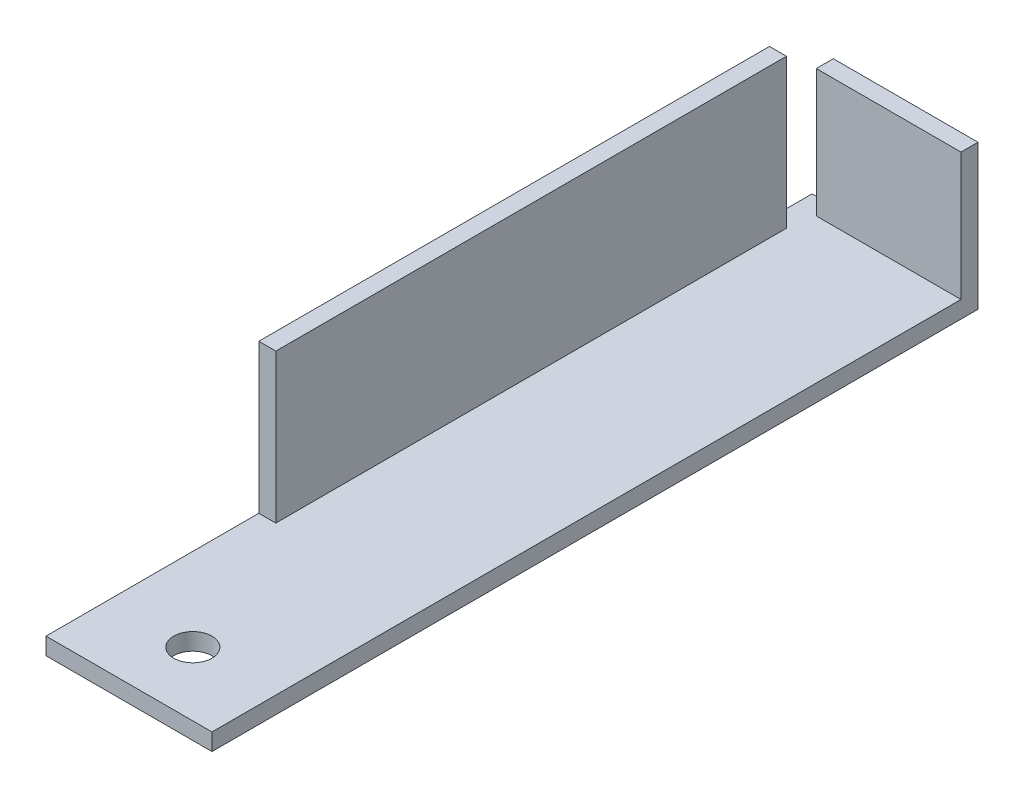
SolidWorks part; units mm, degrees
ref_plane "Front Plane" through (0, 0, 0) normal (0, 0, 1) x (1, 0, 0)
ref_plane "Top Plane" through (0, 0, 0) normal (0, 1, 0) x (1, 0, 0)
ref_plane "Right Plane" through (0, 0, 0) normal (1, 0, 0) x (0, 0, -1)
sketch "Sketch1" plane through (0, 0, 0) normal (0, 0, 1) x (1, 0, 0)
  line L0 (0, 0) -> (0, 19.5)
  line L1 (0, 19.5) -> (2, 19.5)
  line L2 (2, 19.5) -> (2, 2)
  line L3 (2, 2) -> (19.5, 2)
  line L4 (19.5, 2) -> (19.5, 0)
  line L5 (19.5, 0) -> (0, 0)
  dimension "D1" = 19.5
  dimension "D2" = 2
extrude "Boss-Extrude1" add sketch "Sketch1" along normal blind 90
sketch "Sketch8" plane through (2, 0, 0) normal (1, 0, 0) x (0, 0, -1)
  line L0 (-90, 2) -> (0, 2) construction
  line L1 (-90, 19.5) -> (-65, 19.5)
  line L2 (-90, 19.5) -> (-90, 2)
  line L3 (-90, 2) -> (-65, 2)
  line L4 (-65, 19.5) -> (-65, 2)
  line L5 (-90, 2) -> (0, 2) construction
  line L6 (0, 19.5) -> (-5, 19.5)
  line L7 (0, 19.5) -> (0, 2)
  line L8 (0, 2) -> (-5, 2)
  line L9 (-5, 19.5) -> (-5, 2)
  dimension "D1" = 60
  dimension "D2" = 5
extrude "Cut-Extrude1" cut sketch "Sketch8" against normal through all
sketch "Sketch2" plane through (0, 2, 0) normal (0, 1, 0) x (1, 0, 0)
  line L1 (19.5, 0) -> (2.5, 0)
  line L2 (19.5, 0) -> (19.5, -2)
  line L3 (19.5, -2) -> (2.5, -2)
  line L4 (2.5, 0) -> (2.5, -2)
  dimension "D1" = 2
  dimension "D2" = 17
extrude "Boss-Extrude2" add sketch "Sketch2" along normal blind 15
sketch "Sketch9" plane through (0, 2, 0) normal (0, 1, 0) x (1, 0, 0)
  line L0 (19.5, -90) -> (0, -90) construction
  line L1 (0, -82.5) -> (19.5, -82.5) construction
  line L2 (0, -90) -> (0, -65) construction
  line L3 (19.5, -90) -> (19.5, -2) construction
  circle A0 centre (9.75, -82.5) radius 2.25
  dimension "D1" = 4.5
  dimension "D2" = 7.5
extrude "Cut-Extrude2" cut sketch "Sketch9" against normal through all
